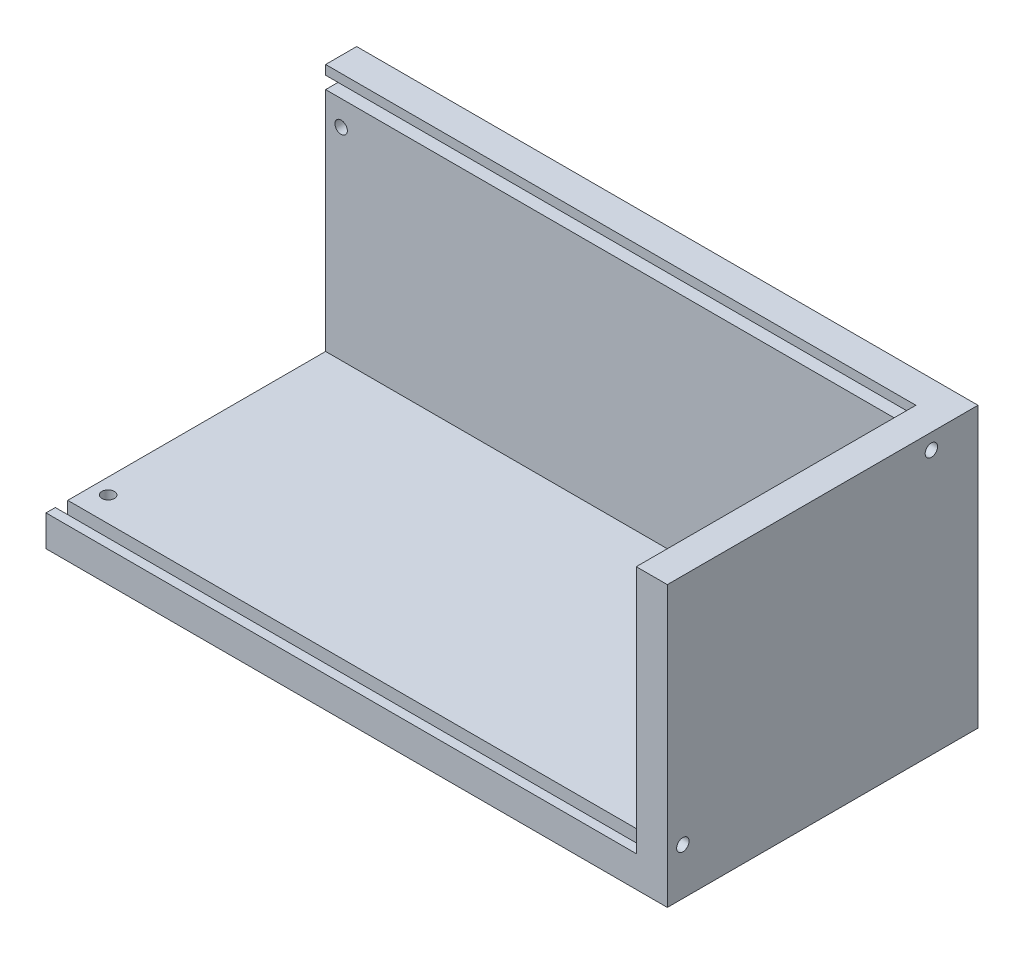
SolidWorks part; units mm, degrees
ref_plane "Alzado" through (0, 0, 0) normal (0, 0, 1) x (1, 0, 0)
ref_plane "Planta" through (0, 0, 0) normal (0, 1, 0) x (1, 0, 0)
ref_plane "Vista lateral" through (0, 0, 0) normal (1, 0, 0) x (0, 0, -1)
sketch "Croquis1" plane through (0, 0, 0) normal (0, 1, 0) x (1, 0, 0)
  line L1 (0, 0) -> (100, 0)
  line L2 (0, 0) -> (0, 50)
  line L3 (0, 50) -> (100, 50)
  line L4 (100, 0) -> (100, 50)
  dimension "D1" = 100
  dimension "D2" = 50
extrude "Saliente-Extruir1" add sketch "Croquis1" along normal blind 5
sketch "Croquis2" plane through (0, 5, 0) normal (0, 1, 0) x (1, 0, 0)
  line L0 (0, 50) -> (0, 0) construction
  line L1 (0, 45) -> (95, 45)
  line L2 (95, 45) -> (95, 0)
  line L3 (0, 0) -> (100, 0) construction
  line L4 (95, 0) -> (100, 0)
  line L5 (100, 0) -> (100, 50)
  line L6 (100, 50) -> (0, 50)
  line L7 (0, 50) -> (0, 45)
  dimension "D1" = 5
  dimension "D2" = 5
extrude "Saliente-Extruir2" add sketch "Croquis2" along normal blind 40
sketch "Croquis3" plane through (0, 0, -45) normal (0, 0, 1) x (1, 0, 0)
  line L0 (0, 45) -> (0, 5) construction
  line L1 (0, 43.5) -> (95, 43.5)
  line L2 (0, 43.5) -> (0, 41.5)
  line L3 (0, 41.5) -> (95, 41.5)
  line L4 (95, 43.5) -> (95, 41.5)
  line L5 (95, 45) -> (95, 5) construction
  line L6 (0, 45) -> (95, 45) construction
  dimension "D1" = 1.5
  dimension "D2" = 2
extrude "Cortar-Extruir1" cut sketch "Croquis3" against normal blind 2
sketch "Croquis4" plane through (0, 5, 0) normal (0, 1, 0) x (1, 0, 0)
  line L0 (0, 45) -> (0, 0) construction
  line L1 (0, 3.5) -> (95, 3.5)
  line L2 (0, 3.5) -> (0, 1.5)
  line L3 (0, 1.5) -> (95, 1.5)
  line L4 (95, 3.5) -> (95, 1.5)
  line L5 (95, 45) -> (95, 0) construction
  line L6 (0, 0) -> (95, 0) construction
  dimension "D1" = 2
  dimension "D2" = 1.5
extrude "Cortar-Extruir2" cut sketch "Croquis4" against normal blind 2
sketch "Croquis5" plane through (95, 0, 0) normal (-1, 0, 0) x (0, 0, 1)
  line L0 (0, 45) -> (0, 5) construction
  line L1 (-1.5, 5) -> (0, 5) construction
  line L2 (-45, 45) -> (0, 45) construction
  line L3 (-45, 41.5) -> (-45, 5) construction
  point P0 (-42.5, 42.5)
  point P1 (-2.5, 7.5)
  dimension "D1" = 2.5
  dimension "D2" = 2.5
  dimension "D3" = 2.5
  dimension "D4" = 2.5
hole_wizard "Diámetro de taladro Ø2.0 (2)1" positions "Croquis3D1" profile "Croquis6" hole size "Ø2.0" standard "DIN" end condition through all
sketch3d "Croquis3D1"
  point P0 (95, 42.5, -42.5)
  point P3 (95, 7.5, -2.5)
sketch "Croquis6" plane through (95, 42.5, -42.5) normal (0, 1, 0) x (0, 0, 1)
  line L0 (0, 0) -> (0, 5)
  line L1 (0, 5) -> (1, 5)
  line L2 (1, 5) -> (1, 0)
  line L5 (1, 0) -> (0, 0)
  line L11 (0, -6.35) -> (0, 107.95) construction
  dimension "Diámetro de taladro hasta el siguiente" = 2
  dimension "Profundidad de taladro hasta el siguiente" = 5
sketch "Croquis7" plane through (0, 0, 0) normal (0, -1, 0) x (1, 0, 0)
  line L0 (0, 0) -> (100, 0) construction
  line L2 (0, -50) -> (0, 0) construction
  point P0 (2.5, -7.5)
  point P5 (0, -10.7206)
  dimension "D1" = 7.5
  dimension "D2" = 2.5
sketch "Croquis8" plane through (0, 0, -50) normal (0, 0, -1) x (-1, 0, 0)
  line L0 (0, 45) -> (0, 0) construction
  line L1 (-100, 45) -> (0, 45) construction
  point P0 (-2.5, 37.5)
  dimension "D1" = 2.5
  dimension "D2" = 7.5
hole_wizard "Diámetro de taladro Ø2.0 (2)2" positions "Croquis3D2" profile "Croquis9" hole size "Ø2.0" standard "DIN"
sketch3d "Croquis3D2"
  point P0 (2.5, 37.5, -50)
  point P3 (2.5, 0, -7.5)
sketch "Croquis9" plane through (2.5, 37.5, -50) normal (1, 0, 0) x (0, 1, 0)
  line L0 (0, 0) -> (0, 10.6009)
  line L1 (0, 10.6009) -> (1, 10)
  line L2 (1, 10) -> (1, 0)
  line L5 (1, 0) -> (0, 0)
  line L10 (0, 10.6009) -> (-1, 10) construction
  line L11 (0, -6.35) -> (0, 107.95) construction
  dimension "Diámetro de taladro" = 2
  dimension "Profundidad de taladro" = 10
  dimension "Ángulo de perforador" = 118
